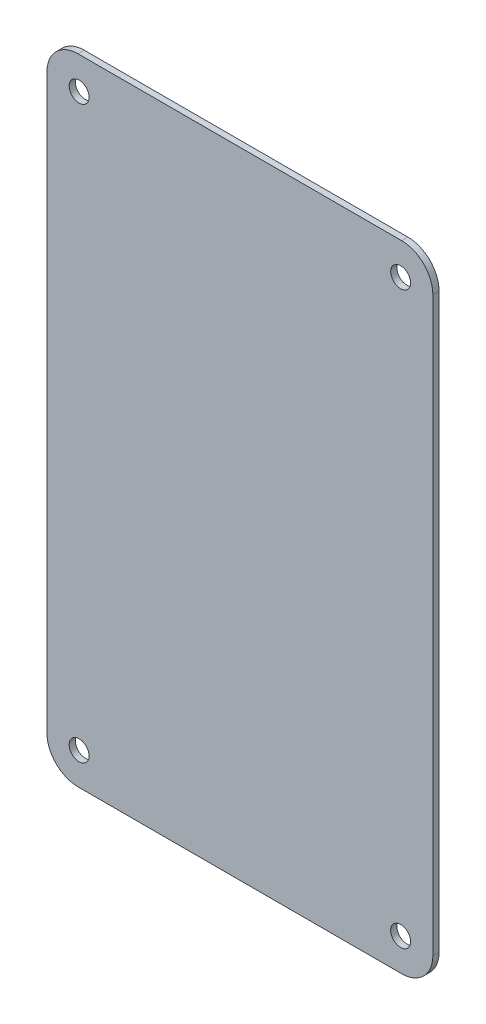
SolidWorks part; units mm, degrees
ref_plane "Front" through (0, 0, 0) normal (0, 0, 1) x (1, 0, 0)
ref_plane "Top" through (0, 0, 0) normal (0, 1, 0) x (1, 0, 0)
ref_plane "Right" through (0, 0, 0) normal (1, 0, 0) x (0, 0, -1)
sketch "Esquisse1" plane through (0, 0, 0) normal (0, 0, 1) x (1, 0, 0)
  line L0 (26.9719, 14.7074) -> (78.9719, 14.7074) construction
  line L5 (83.9719, 19.7074) -> (83.9719, 111.7074) construction
  line L6 (78.9719, 116.7074) -> (26.9719, 116.7074) construction
  line L7 (21.9719, 111.7074) -> (21.9719, 19.7074) construction
  line L8 (26.9719, 14.7074) -> (78.9719, 14.7074)
  line L9 (83.9719, 19.7074) -> (83.9719, 111.7074)
  line L10 (78.9719, 116.7074) -> (26.9719, 116.7074)
  line L11 (21.9719, 111.7074) -> (21.9719, 19.7074)
  arc A0 (21.9719, 19.7074) -> (26.9719, 14.7074) centre (26.9719, 19.7074) ccw construction
  arc A1 (78.9719, 14.7074) -> (83.9719, 19.7074) centre (78.9719, 19.7074) ccw construction
  arc A2 (83.9719, 111.7074) -> (78.9719, 116.7074) centre (78.9719, 111.7074) ccw construction
  arc A3 (26.9719, 116.7074) -> (21.9719, 111.7074) centre (26.9719, 111.7074) ccw construction
  arc A4 (21.9719, 19.7074) -> (26.9719, 14.7074) centre (26.9719, 19.7074) ccw
  arc A5 (78.9719, 14.7074) -> (83.9719, 19.7074) centre (78.9719, 19.7074) ccw
  arc A6 (83.9719, 111.7074) -> (78.9719, 116.7074) centre (78.9719, 111.7074) ccw
  arc A7 (26.9719, 116.7074) -> (21.9719, 111.7074) centre (26.9719, 111.7074) ccw
extrude "Boss.-Extru.1" add sketch "Esquisse1" along normal blind 1
sketch "Esquisse2" plane through (0, 0, 1) normal (0, 0, 1) x (1, 0, 0)
  circle A0 centre (27.1435, 19.8789) radius 1.6
  circle A1 centre (78.8003, 19.8789) radius 1.6
  circle A2 centre (27.1435, 111.5358) radius 1.6
  circle A3 centre (78.8003, 111.5358) radius 1.6
  point P8 (78.8003, 19.8789)
  point P10 (27.1435, 19.8789)
  point P12 (27.1435, 111.5358)
  point P14 (73.4875, 120.3837)
  point P15 (78.8003, 111.5358)
  dimension "D1" = 3.2
extrude "Enlèv. mat.-Extru.1" cut sketch "Esquisse2" against normal through all both and the other way through all
